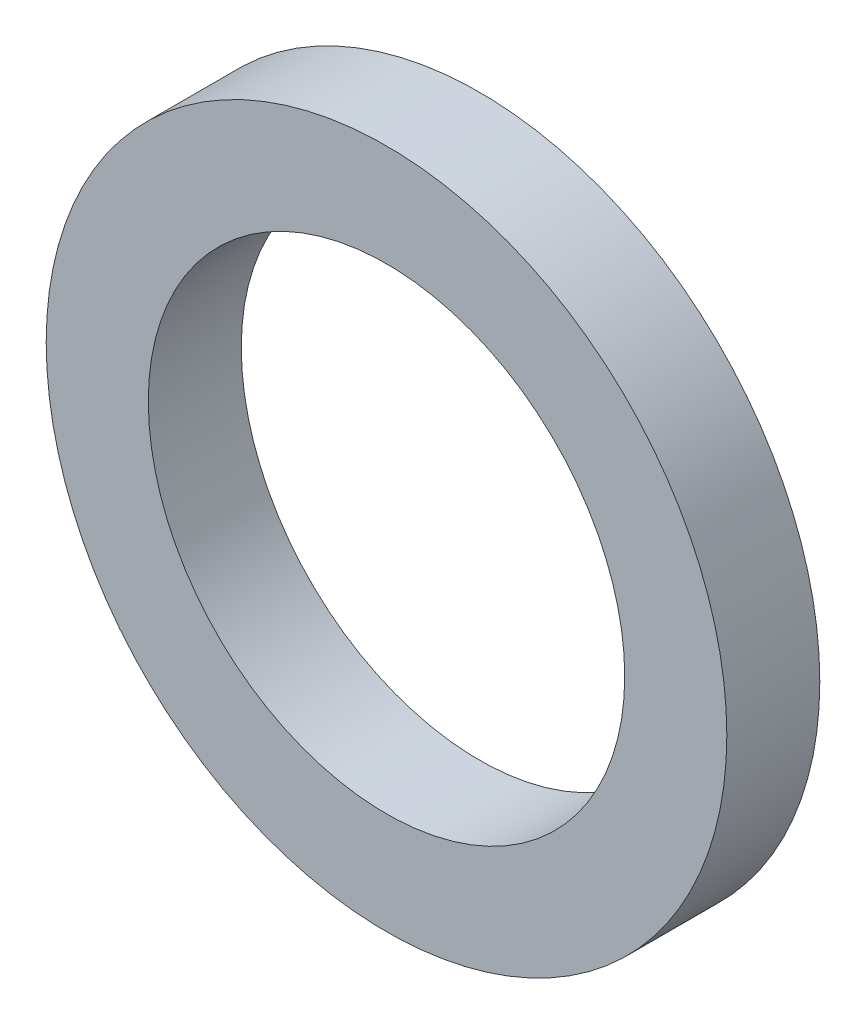
SolidWorks part; units mm, degrees
ref_plane "Plan de face" through (0, 0, 0) normal (0, 0, 1) x (1, 0, 0)
ref_plane "Plan de dessus" through (0, 0, 0) normal (0, 1, 0) x (1, 0, 0)
ref_plane "Plan de droite" through (0, 0, 0) normal (1, 0, 0) x (0, 0, -1)
sketch "Esquisse1" plane through (0, 0, 0) normal (0, 0, 1) x (1, 0, 0)
  circle A0 centre (0, 0) radius 17.5
  circle A1 centre (0, 0) radius 25
  dimension "D1" = 35
  dimension "D2" = 50
extrude "Boss.-Extru.1" add sketch "Esquisse1" along normal blind 6.83
